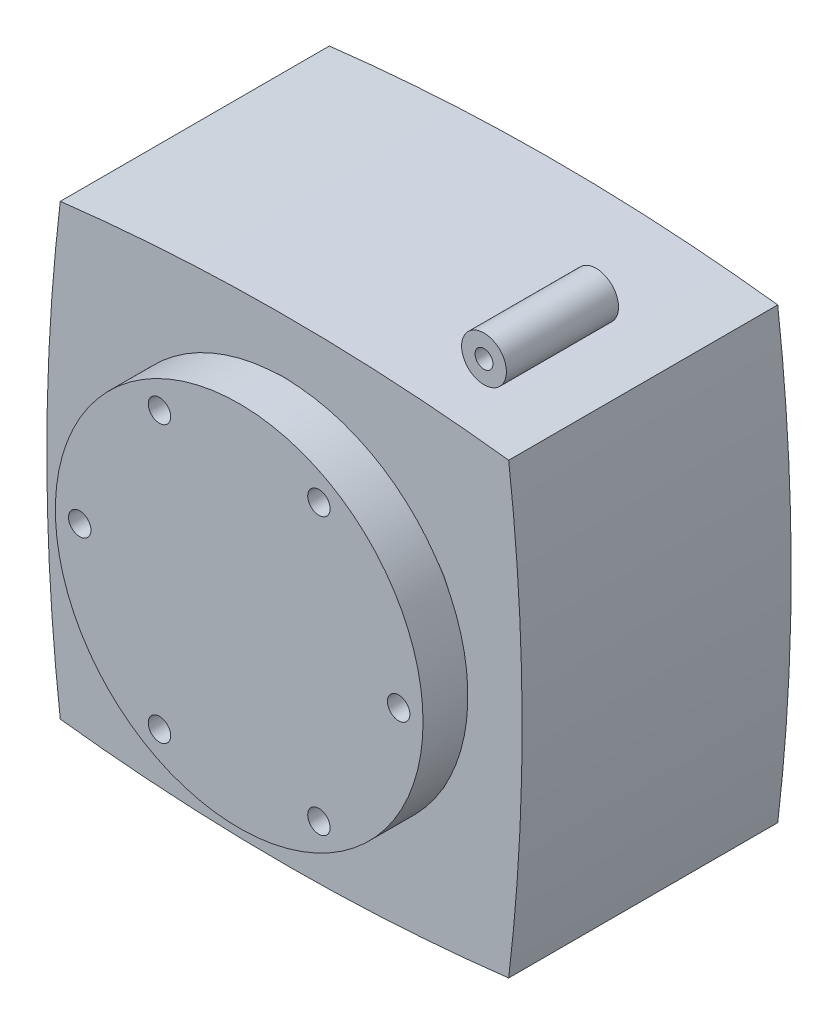
SolidWorks part; units mm, degrees
ref_plane "Front Plane" through (0, 0, 0) normal (0, 0, 1) x (1, 0, 0)
ref_plane "Top Plane" through (0, 0, 0) normal (0, 1, 0) x (1, 0, 0)
ref_plane "Right Plane" through (0, 0, 0) normal (1, 0, 0) x (0, 0, -1)
sketch "Sketch1" plane through (0, 0, 0) normal (0, 0, 1) x (1, 0, 0)
  circle A0 centre (0, 0) radius 41
  dimension "D1" = 82
extrude "Boss-Extrude1" add sketch "Sketch1" along normal blind 10 contours A0
sketch "Sketch2" plane through (0, 0, 0) normal (0, 0, -1) x (-1, 0, 0)
  line L0 (-35.56, 0) -> (35.56, 0) construction
  line L1 (0, 0) -> (0, -41) construction
  line L2 (0, 0) -> (0, 41) construction
  line L3 (0, -30.7959) -> (17.78, -30.7959) construction
  line L4 (0, -30.7959) -> (-17.78, -30.7959) construction
  circle A0 centre (-35.56, 0) radius 2.5
  circle A1 centre (35.56, 0) radius 2.5
  circle A2 centre (0, 0) radius 38.06 construction
  circle A3 centre (0, 0) radius 33.06 construction
  circle A4 centre (-17.78, -30.7959) radius 2.5
  circle A5 centre (17.78, -30.7959) radius 2.5
  circle A6 centre (0, 0) radius 41 construction
  circle A7 centre (-17.78, 30.7959) radius 2.5
  circle A8 centre (17.78, 30.7959) radius 2.5
  point P4 (0, 0)
  dimension "D2" = 5
  dimension "D3" = 66.12
  dimension "D4" = 76.12
  dimension "D6" = 5
  dimension "D7" = 5
  dimension "D1" = 71.12
  dimension "D5" = 35.56
extrude "Cut-Extrude1" cut sketch "Sketch2" against normal blind 10
sketch "Sketch3" plane through (0, 0, 0) normal (0, 0, -1) x (-1, 0, 0)
  circle A1 centre (0, 0) radius 47.5 construction
  arc A2 (22.2693, -27.7235) -> (12.8746, -33.1475) centre (17.78, -30.7959) ccw
  circle A3 centre (0, 0) radius 42.5 construction
  arc A5 (-12.8746, -33.1475) -> (-22.2693, -27.7235) centre (-17.78, -30.7959) ccw
  circle A12 centre (0, 0) radius 41
  arc A13 (-35.1439, -5.4241) -> (-35.1439, 5.4241) centre (-35.56, 0) ccw
  arc A14 (-22.2693, 27.7235) -> (-12.8746, 33.1475) centre (-17.78, 30.7959) ccw
  arc A15 (12.8746, 33.1475) -> (22.2693, 27.7235) centre (17.78, 30.7959) ccw
  arc A16 (35.1439, 5.4241) -> (35.1439, -5.4241) centre (35.56, 0) ccw
  arc A17 (22.2693, -27.7235) -> (35.1439, -5.4241) centre (22.9665, -13.2597) ccw
  circle A19 centre (0, 0) radius 41 construction
  arc A25 (-22.2693, 27.7235) -> (-35.1439, 5.4241) centre (-22.9665, 13.2597) ccw
  arc A26 (35.1439, 5.4241) -> (22.2693, 27.7235) centre (22.9665, 13.2597) ccw
  arc A28 (-35.1439, -5.4241) -> (-22.2693, -27.7235) centre (-22.9665, -13.2597) ccw
  arc A29 (-12.8746, -33.1475) -> (12.8746, -33.1475) centre (0, -26.5195) ccw
  arc A30 (12.8746, 33.1475) -> (-12.8746, 33.1475) centre (0, 26.5195) ccw
  dimension "D1" = 95
  dimension "D2" = 85
extrude "Boss-Extrude3" add sketch "Sketch3" along normal blind 0.1 contours A15 A30 A14 A25 A13 A28 A5 A29 A2 A17 A16 A26
sketch "Sketch4" plane through (0, 0, -0.1) normal (0, 0, -1) x (-1, 0, 0)
  line L1 (-50, 50) -> (50, 50)
  line L2 (-50, 50) -> (-50, -50)
  line L3 (-50, -50) -> (50, -50)
  line L4 (50, 50) -> (50, -50)
  dimension "D1" = 50
  dimension "D2" = 50
  dimension "D3" = 50
  dimension "D4" = 50
extrude "Boss-Extrude4" add sketch "Sketch4" along normal blind 10
sketch "Sketch5" plane through (0, 0, -10.1) normal (0, 0, -1) x (-1, 0, 0)
  line L1 (-50, 50) -> (50, 50)
  line L2 (-50, 50) -> (-50, -50)
  line L3 (-50, -50) -> (50, -50)
  line L4 (50, 50) -> (50, -50)
  line L5 (-46, 46) -> (46, 46)
  line L6 (-46, 46) -> (-46, -46)
  line L7 (-46, -46) -> (46, -46)
  line L8 (46, 46) -> (46, -46)
  dimension "D1" = 4
  dimension "D2" = 4
  dimension "D3" = 4
  dimension "D4" = 4
extrude "Boss-Extrude5" add sketch "Sketch5" along normal blind 50
sketch "Sketch7" plane through (0, 0, -60.1) normal (0, 0, -1) x (-1, 0, 0)
  line L1 (-46, 46) -> (46, 46)
  line L2 (-46, 46) -> (-46, -46)
  line L3 (-46, -46) -> (46, -46)
  line L4 (46, 46) -> (46, -46)
  spline S0 degree 2 poles (-50, 50) (0, 56) (50, 50) knots 0 0 0 1 1 1
  spline S1 degree 2 poles (50, 50) (56, 0) (50, -50) knots 0 0 0 1 1 1
  spline S2 degree 2 poles (-50, -50) (0, -56) (50, -50) knots 0 0 0 1 1 1
  spline S3 degree 2 poles (-50, 50) (-56, 0) (-50, -50) knots 0 0 0 1 1 1
extrude "Boss-Extrude6" add sketch "Sketch7" against normal up to surface (60 mm away) up to face at (0, 0, -0.1)
sketch "Sketch8" plane through (0, 0, -60.1) normal (0, 0, -1) x (-1, 0, 0)
  line L0 (-46, -46) -> (46, -46) construction
  line L1 (46, -46) -> (46, 46) construction
  line L2 (-46, 46) -> (-46, -46) construction
  line L3 (46, 46) -> (-46, 46) construction
  line L4 (-53, 0) -> (-46, 0) construction
  line L5 (-46, 46) -> (-46, -46) construction
  line L6 (0, 46) -> (0, 53) construction
  line L7 (46, 0) -> (53, 0) construction
  line L8 (0, -46) -> (0, -53) construction
  line L9 (-46, -46) -> (46, -46) construction
  circle A0 centre (-47, 0) radius 2
  circle A1 centre (49.5, 0) radius 2
  circle A2 centre (0, 49.5) radius 2
  circle A3 centre (0, -49.5) radius 2
  circle A4 centre (-47, 0) radius 6 construction
  circle A5 centre (0, 49.5) radius 3.5 construction
  circle A6 centre (0, 0) radius 53 construction
  circle A7 centre (49.5, 0) radius 3.5 construction
  circle A8 centre (0, -49.5) radius 3.5 construction
  parabola Q1 (-50, 50) -> (-50, -50) focus (155.3333, 0) apex (-53, 0) construction
  parabola Q3 (50, 50) -> (-50, 50) focus (0, -155.3333) apex (0, 53) construction
  parabola Q4 (50, -50) -> (50, 50) focus (-155.3333, 0) apex (53, 0) construction
  parabola Q5 (-50, -50) -> (50, -50) focus (0, 155.3333) apex (0, -53) construction
  point P10 (0, -46)
  point P13 (46, 0)
  point P16 (-46, 0)
  point P19 (0, 46)
  point P50 (0, -49.5)
  point P51 (49.5, 0)
  point P52 (0, 49.5)
  dimension "D1" = 106
  dimension "D2" = 4
  dimension "D3" = 4
  dimension "D4" = 4
  dimension "D5" = 4
  dimension "D6" = 6
sketch "Sketch10" plane through (0, 0, 10) normal (0, 0, 1) x (1, 0, 0)
  circle A0 centre (-17.78, 30.7959) radius 2.5
  circle A1 centre (17.78, 30.7959) radius 2.5
  circle A2 centre (35.56, 0) radius 2.5
  circle A3 centre (17.78, -30.7959) radius 2.5
  circle A4 centre (-17.78, -30.7959) radius 2.5
  circle A5 centre (-35.56, 0) radius 2.5
extrude "Cut-Extrude3" cut sketch "Sketch10" against normal through all
sketch "Sketch11" plane through (0, 0, -10.1) normal (0, 0, -1) x (-1, 0, 0)
  circle A0 centre (-34.5, 56.8172) radius 2
  circle A1 centre (37.5, 43.8172) radius 2
  circle A2 centre (29, -17.6028) radius 2
  circle A3 centre (-34.5, 1.2572) radius 2
  circle A4 centre (-34.5, 1.2572) radius 5
  circle A5 centre (29, -17.6028) radius 5
  circle A6 centre (37.5, 43.8172) radius 5
  circle A7 centre (-34.5, 56.8172) radius 5
  point P11 (0, 0)
  point P13 (43, 32.6372)
  dimension "D1" = 4
  dimension "D2" = 72
  dimension "D3" = 61.42
  dimension "D5" = 63.5
  dimension "D6" = 55.56
  dimension "D8" = 13
extrude "Boss-Extrude7" add sketch "Sketch11" along normal blind 25
